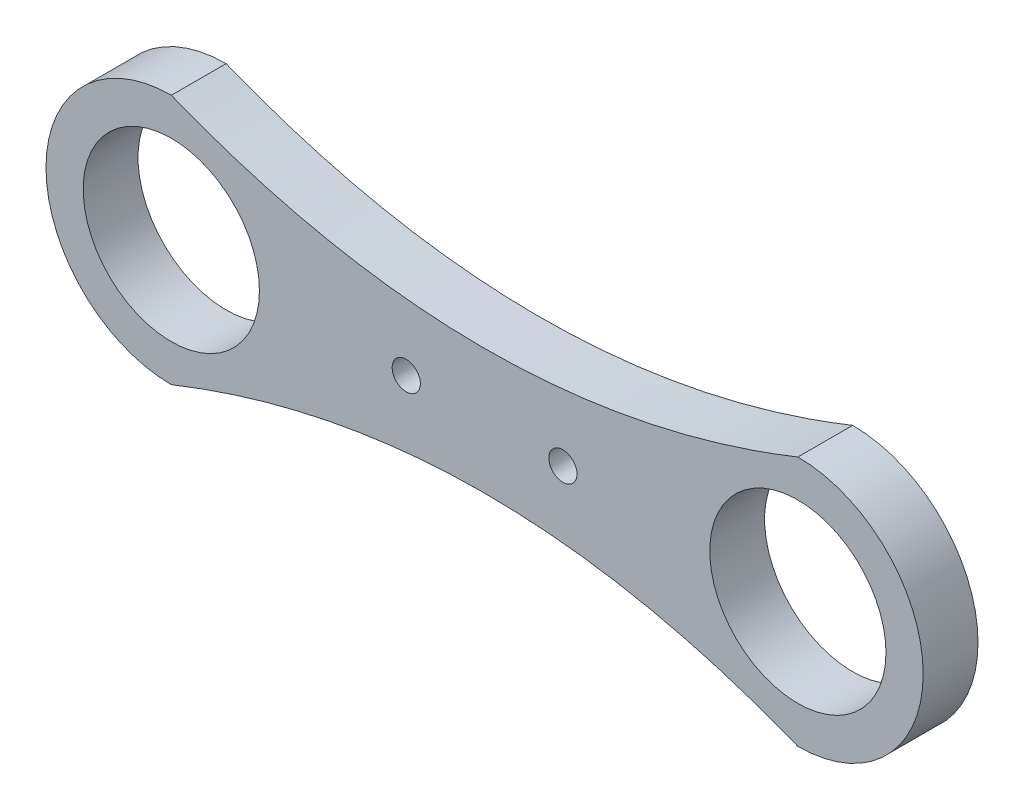
SolidWorks part; units mm, degrees
ref_plane "Plan de face" through (0, 0, 0) normal (0, 0, 1) x (1, 0, 0)
ref_plane "Plan de dessus" through (0, 0, 0) normal (0, 1, 0) x (1, 0, 0)
ref_plane "Plan de droite" through (0, 0, 0) normal (1, 0, 0) x (0, 0, -1)
sketch "Esquisse1" plane through (0, 0, 0) normal (0, 0, 1) x (1, 0, 0)
  line L0 (0, 0) -> (80, 0) construction
  line L1 (0, 16) -> (80, 16)
  line L2 (0, -16) -> (80, -16)
  line L3 (0, -16) -> (40, 0) construction
  line L4 (40, 0) -> (80, -16) construction
  line L5 (0, 16) -> (40, 0) construction
  line L6 (40, 0) -> (80, 16) construction
  arc A0 (0, 16) -> (0, -16) centre (0, 0) ccw
  arc A1 (80, -16) -> (80, 16) centre (80, 0) ccw
  circle A2 centre (0, 0) radius 11.25
  circle A3 centre (80, 0) radius 11.25
  spline S0 degree 2 poles (0, 16) (40, 0) (80, 16) knots 0 0 0 1 1 1
  spline S1 degree 2 poles (0, -16) (40, 0) (80, -16) knots 0 0 0 1 1 1
  point P3 (40, 0)
  point P12 (40, -16)
  dimension "D2" = 22.5
  dimension "D3" = 22.5
  dimension "D1" = 80
  dimension "D4" = 32
extrude "Boss.-Extru.1" add sketch "Esquisse1" along normal blind 7 contours A0 S1 A1 S0 A3 A2
sketch "Esquisse2" plane through (0, 0, 7) normal (0, 0, 1) x (1, 0, 0)
  line L0 (0, 0) -> (80, 0) construction
  line L1 (80, 0) -> (80, 11.25) construction
  line L2 (80, 11.25) -> (80, -11.25) construction
  circle A0 centre (80, 0) radius 11.25 construction
  circle A1 centre (30, 0) radius 1.8
  circle A2 centre (50, 0) radius 1.8
  point P14 (40, 0)
  dimension "D1" = 3.6
  dimension "D2" = 3.6
  dimension "D3" = 20
  dimension "D4" = 10
extrude "Enlèv. mat.-Extru.1" cut sketch "Esquisse2" against normal blind 10
